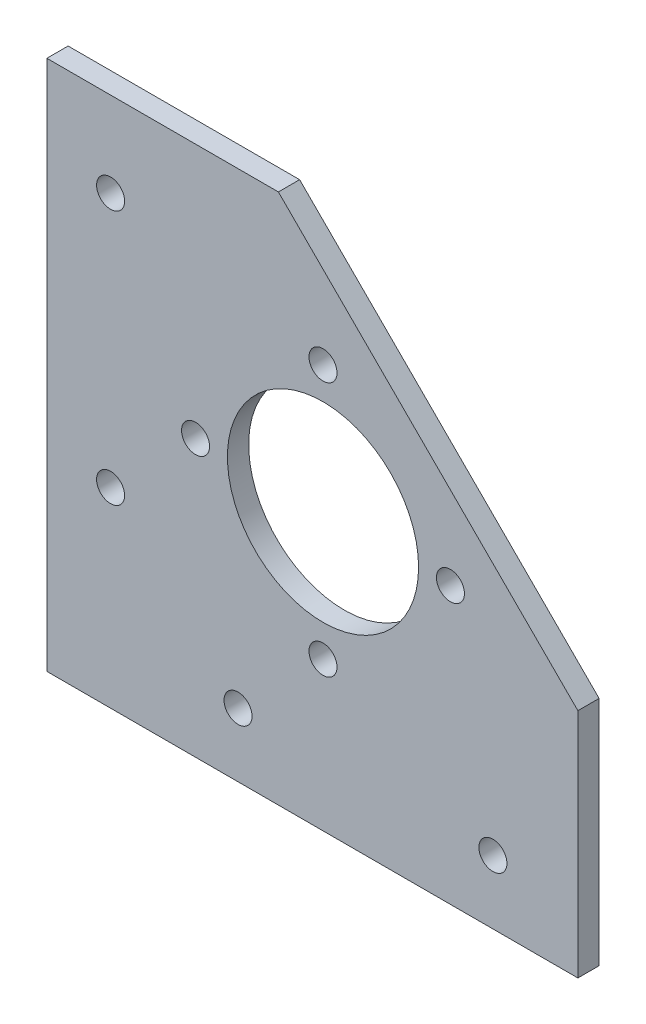
SolidWorks part; units mm, degrees
ref_plane "Спереди" through (0, 0, 0) normal (0, 0, 1) x (1, 0, 0)
ref_plane "Сверху" through (0, 0, 0) normal (0, 1, 0) x (1, 0, 0)
ref_plane "Справа" through (0, 0, 0) normal (1, 0, 0) x (0, 0, -1)
sketch "Эскиз1" plane through (0, 0, 0) normal (0, 0, 1) x (1, 0, 0)
  line L0 (0, 0) -> (0, 125)
  line L1 (54.4975, 125) -> (125, 54.4975)
  line L2 (125, 0) -> (0, 0)
  line L3 (24.6142, 30) -> (108.2861, 30) construction
  line L4 (65, 65) -> (89.7487, 89.7487) construction
  line L5 (0, 125) -> (54.4975, 125)
  line L6 (125, 54.4975) -> (125, 0)
  circle A0 centre (65, 65) radius 35 construction
  circle A1 centre (65, 65) radius 22.5
  dimension "D1" = 70
  dimension "D3" = 45
  dimension "D2" = 30
  dimension "D4" = 125
  dimension "D5" = 125
extrude "Бобышка-Вытянуть1" add sketch "Эскиз1" along normal blind 5
hole_wizard "Отверстие с зазором M61" positions "Эскиз3" profile "Эскиз2" hole size "M6" standard "DIN"
sketch "Эскиз3" plane through (0, 0, 0) normal (0, 0, -1) x (-1, 0, 0)
  line L1 (-65, 95) -> (-95, 65)
  line L2 (-65, 95) -> (-35, 65)
  line L3 (-35, 65) -> (-65, 35)
  line L4 (-95, 65) -> (-65, 35)
  line L5 (-54.4975, 125) -> (-125, 54.4975) construction
  line L6 (-15, 164.4975) -> (-15, 15)
  line L7 (-15, 15) -> (-164.4975, 15)
  line L9 (0, 0) -> (0, 125) construction
  line L10 (-125, 0) -> (0, 0) construction
  circle A0 centre (-65, 65) radius 30
  circle A1 centre (-65, 65) radius 22.5 construction
  point P0 (-95, 65)
  point P1 (-65, 95)
  point P3 (-35, 65)
  point P5 (-65, 35)
  point P7 (-105, 15)
  point P9 (-45, 15)
  point P11 (-15, 45)
  point P13 (-15, 105)
  dimension "D1" = 60
  dimension "D2" = 15
  dimension "D3" = 15
  dimension "D4" = 60
  dimension "D5" = 60
  dimension "D6" = 45
  dimension "D7" = 45
sketch "Эскиз2" plane through (95, 65, 0) normal (1, 0, 0) x (0, 1, 0)
  line L0 (0, 0) -> (0, 11.9828)
  line L1 (0, 11.9828) -> (3.3, 10)
  line L2 (3.3, 10) -> (3.3, 0)
  line L5 (3.3, 0) -> (0, 0)
  line L10 (0, 11.9828) -> (-3.3, 10) construction
  line L11 (0, -6.35) -> (0, 107.95) construction
  dimension "Диаметр отверстия" = 6.6
  dimension "Глубина отверстия" = 10
  dimension "Угол заточки сверла" = 118
fillet "Скругление1" [suppressed] radius 100
